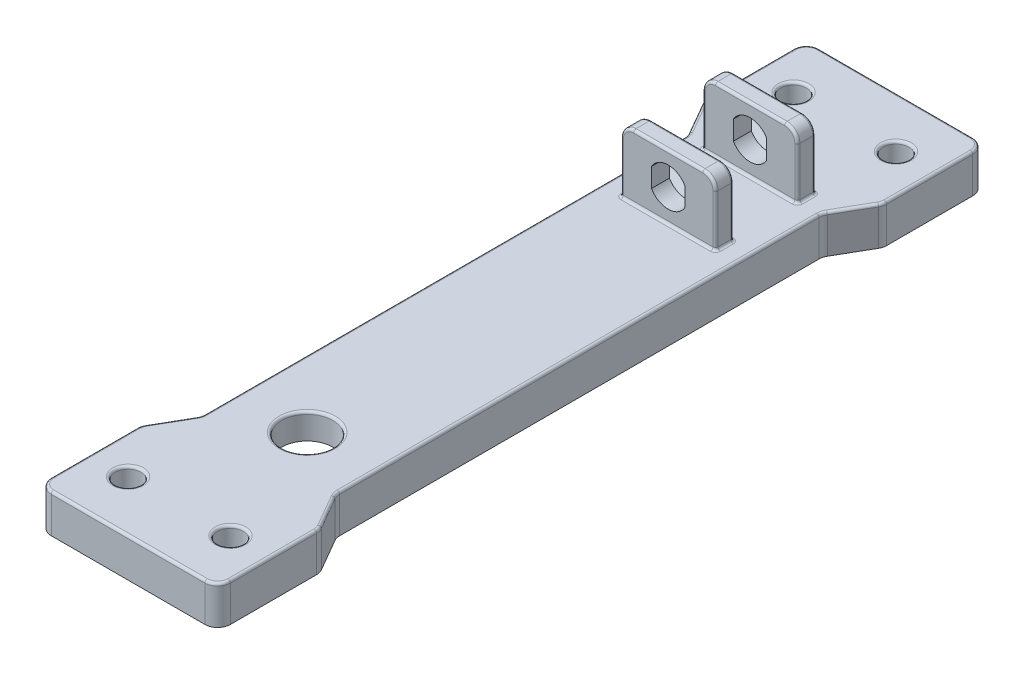
SolidWorks part; units mm, degrees
ref_plane "Front Plane" through (0, 0, 0) normal (0, 0, 1) x (1, 0, 0)
ref_plane "Top Plane" through (0, 0, 0) normal (0, 1, 0) x (1, 0, 0)
ref_plane "Right Plane" through (0, 0, 0) normal (1, 0, 0) x (0, 0, -1)
sketch "Sketch1" plane through (0, 0, 0) normal (0, 1, 0) x (1, 0, 0)
  line L0 (0, 150) -> (0, -150) construction
  line L1 (-35, -150) -> (35, -150)
  line L2 (-35, -150) -> (-35, -110)
  line L3 (-35, 150) -> (35, 150)
  line L4 (35, -150) -> (35, -110)
  line L5 (-35, -150) -> (35, 150) construction
  line L6 (-35, 150) -> (35, -150) construction
  line L7 (-35, 110) -> (-26.3397, 95)
  line L8 (-26.3397, 95) -> (-26.3397, -95)
  line L9 (-26.3397, -95) -> (-35, -110)
  line L10 (26.3397, -95) -> (35, -110)
  line L11 (26.3397, 95) -> (26.3397, -95)
  line L12 (35, 110) -> (26.3397, 95)
  line L13 (-35, 110) -> (-35, 150)
  line L14 (35, 110) -> (35, 150)
  point P0 (0, 0)
  dimension "D1" = 300
  dimension "D2" = 70
  dimension "D3" = 40
  dimension "D4" = 40
  dimension "D5" = 190
  dimension "D6" = 30
extrude "Boss-Extrude1" add sketch "Sketch1" against normal blind 15
fillet "Fillet1" radius 5 12 edges at (35, -7.5, -150) (-35, -7.5, -150) (-35, -7.5, -110) (-26.3397, -7.5, -95) (-26.3397, -7.5, 95) (-35, -7.5, 110) (-35, -7.5, 150) (35, -7.5, 110) (26.3397, -7.5, 95) (26.3397, -7.5, -95) (35, -7.5, -110) (35, -7.5, 150)
sketch "Sketch2" plane through (0, -15, 0) normal (0, -1, 0) x (1, 0, 0)
  line L24 (-25, -140) -> (25, -140)
  line L25 (25, -140) -> (25, -112.6795)
  line L26 (25, -112.6795) -> (18.3494, -101.1603)
  line L27 (16.3397, -93.6603) -> (16.3397, 93.6603)
  line L28 (18.3494, 101.1603) -> (25, 112.6795)
  line L29 (25, 112.6795) -> (25, 140)
  line L30 (25, 140) -> (-25, 140)
  line L31 (-25, 140) -> (-25, 112.6795)
  line L32 (-25, 112.6795) -> (-18.3494, 101.1603)
  line L33 (-16.3397, 93.6603) -> (-16.3397, -93.6603)
  line L34 (-18.3494, -101.1603) -> (-25, -112.6795)
  line L35 (-25, -112.6795) -> (-25, -140)
  line L36 (-25, -140) -> (25, -140)
  line L37 (25, -140) -> (25, -112.6795)
  line L38 (25, -112.6795) -> (18.3494, -101.1603)
  line L39 (16.3397, -93.6603) -> (16.3397, 93.6603)
  line L40 (18.3494, 101.1603) -> (25, 112.6795)
  line L41 (25, 112.6795) -> (25, 140)
  line L42 (25, 140) -> (-25, 140)
  line L43 (-25, 140) -> (-25, 112.6795)
  line L44 (-25, 112.6795) -> (-18.3494, 101.1603)
  line L45 (-16.3397, 93.6603) -> (-16.3397, -93.6603)
  line L46 (-18.3494, -101.1603) -> (-25, -112.6795)
  line L47 (-25, -112.6795) -> (-25, -140)
  arc A24 (16.3397, -93.6603) -> (18.3494, -101.1603) centre (31.3397, -93.6603) ccw
  arc A25 (18.3494, 101.1603) -> (16.3397, 93.6603) centre (31.3397, 93.6603) ccw
  arc A26 (-16.3397, 93.6603) -> (-18.3494, 101.1603) centre (-31.3397, 93.6603) ccw
  arc A27 (-18.3494, -101.1603) -> (-16.3397, -93.6603) centre (-31.3397, -93.6603) ccw
  arc A28 (16.3397, -93.6603) -> (18.3494, -101.1603) centre (31.3397, -93.6603) ccw
  arc A29 (18.3494, 101.1603) -> (16.3397, 93.6603) centre (31.3397, 93.6603) ccw
  arc A30 (-16.3397, 93.6603) -> (-18.3494, 101.1603) centre (-31.3397, 93.6603) ccw
  arc A31 (-18.3494, -101.1603) -> (-16.3397, -93.6603) centre (-31.3397, -93.6603) ccw
  dimension "D1" = 10
extrude "Cut-Extrude1" cut sketch "Sketch2" against normal blind 5
sketch "Sketch3" plane through (0, 0, 0) normal (0, 1, 0) x (1, 0, 0)
  line L0 (0, 5.8442) -> (0, 177.7311) construction
  line L1 (30, 150) -> (-30, 150) construction
  line L2 (-18.5, 93) -> (18.5, 93)
  line L3 (-18.5, 93) -> (-18.5, 100)
  line L4 (-18.5, 100) -> (18.5, 100)
  line L5 (18.5, 93) -> (18.5, 100)
  line L6 (-18.5, 93) -> (18.5, 100) construction
  line L7 (-18.5, 100) -> (18.5, 93) construction
  line L8 (-18.5, 61) -> (18.5, 61)
  line L9 (-18.5, 61) -> (-18.5, 68)
  line L10 (-18.5, 68) -> (18.5, 68)
  line L11 (18.5, 61) -> (18.5, 68)
  line L12 (-18.5, 61) -> (18.5, 68) construction
  line L13 (-18.5, 68) -> (18.5, 61) construction
  point P3 (0, 96.5)
  point P8 (0, 64.5)
  dimension "D1" = 7
  dimension "D2" = 37
  dimension "D3" = 25
  dimension "D4" = 50
extrude "Boss-Extrude2" add sketch "Sketch3" along normal blind 25
fillet "Fillet2" radius 5 4 edges at (-18.5, 25, -64.5) (18.5, 25, -64.5) (18.5, 25, -96.5) (-18.5, 25, -96.5)
fillet "Fillet3" radius 1 28 edges at (18.5, 0, -64.5) (0, 0, -68) (-18.5, 0, -64.5) (0, 0, -61) (0, 25, -68) (0, 25, -61) (-18.5, 10, -61) (-18.5, 10, -68) (18.5, 10, -68) (18.5, 0, -96.5) (0, 0, -100) (-18.5, 0, -96.5) (0, 0, -93) (0, 25, -100) (0, 25, -93) (18.5, 10, -93) (-18.5, 10, -93) (-18.5, 10, -100) (18.5, 10, -100) (17.0355, 23.5355, -61) (-17.0355, 23.5355, -61) (17.0355, 23.5355, -68) (-17.0355, 23.5355, -68) (-17.0355, 23.5355, -100) (17.0355, 23.5355, -100) (-17.0355, 23.5355, -93) (17.0355, 23.5355, -93) (18.5, 10, -61)
sketch "Sketch4" plane through (0, 0, -61) normal (0, 0, 1) x (1, 0, 0)
  line L0 (0, 1) -> (0, 24) construction
  line L1 (-17.5, 1) -> (17.5, 1) construction
  line L2 (13.5, 24) -> (-13.5, 24) construction
  line L3 (-30, 0) -> (30, 0) construction
  line L4 (-6.5, 16.2417) -> (-6.5, 8.7583)
  line L5 (6.5, 16.2417) -> (6.5, 8.7583)
  arc A0 (-6.5, 8.7583) -> (6.5, 8.7583) centre (0, 12.5) ccw
  arc A1 (6.5, 16.2417) -> (-6.5, 16.2417) centre (0, 12.5) ccw
  dimension "D1" = 12.5
  dimension "D3" = 15
  dimension "D2" = 6.5
extrude "Cut-Extrude2" cut sketch "Sketch4" against normal through all
sketch "Sketch5" plane through (0, 0, 0) normal (0, 1, 0) x (1, 0, 0)
  line L0 (0, 150) -> (0, -150) construction
  line L1 (30, 150) -> (-30, 150) construction
  line L2 (-30, -150) -> (30, -150) construction
  line L3 (0, 0) -> (58.1018, 0) construction
  circle A0 centre (-20, 130) radius 5
  circle A1 centre (20, 130) radius 5
  circle A2 centre (20, -130) radius 5
  circle A3 centre (-20, -130) radius 5
  dimension "D4" = 10
  dimension "D1" = 20
  dimension "D2" = 20
  dimension "D3" = 20
extrude "Cut-Extrude3" cut sketch "Sketch5" against normal through all
sketch "Sketch6" plane through (0, 0, 0) normal (0, 1, 0) x (1, 0, 0)
  line L0 (-30, -150) -> (30, -150) construction
  circle A0 centre (0, -80) radius 10
  dimension "D1" = 20
  dimension "D2" = 70
extrude "Cut-Extrude4" cut sketch "Sketch6" against normal through all
fillet "Fillet4" radius 1 29 edges at (34.8296, 0, -110.0457) (30.6699, 0, -102.5) (26.5101, 0, -94.9543) (26.3397, 0, 0) (26.5101, 0, 94.9543) (30.6699, 0, 102.5) (34.8296, 0, 110.0457) (35, 0, 128.1699) (33.5355, 0, 148.5355) (0, 0, 150) (-33.5355, 0, 148.5355) (-35, 0, 128.1699) (-34.8296, 0, 110.0457) (-30.6699, 0, 102.5) (-26.5101, 0, 94.9543) (-26.3397, 0, 0) (-26.5101, 0, -94.9543) (-30.6699, 0, -102.5) (-34.8296, 0, -110.0457) (-35, 0, -128.1699) (-33.5355, 0, -148.5355) (0, 0, -150) (33.5355, 0, -148.5355) (35, 0, -128.1699) (-20, 0, -125) (20, 0, -125) (20, 0, 125) (-20, 0, 125) (0, 0, 90)
